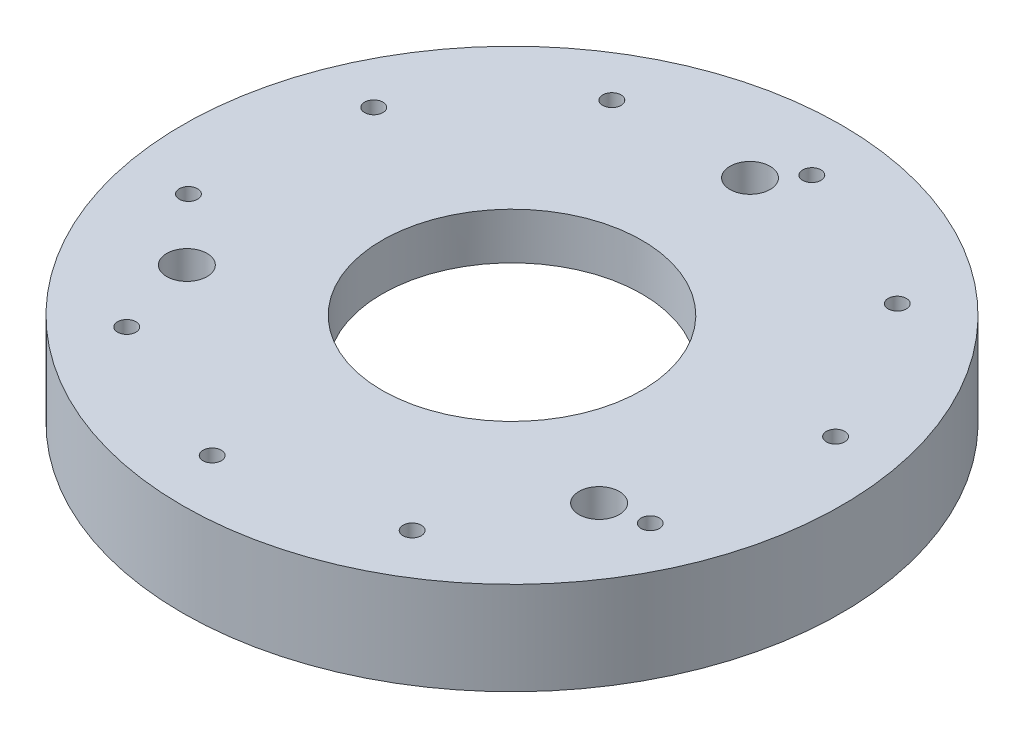
SolidWorks part; units mm, degrees
material "6061-T6 (SS)"
ref_plane "Front Plane" through (0, 0, 0) normal (0, 0, 1) x (1, 0, 0)
ref_plane "Top Plane" through (0, 0, 0) normal (0, 1, 0) x (1, 0, 0)
ref_plane "Right Plane" through (0, 0, 0) normal (1, 0, 0) x (0, 0, -1)
sketch "Sketch1" plane through (0, 0, 0) normal (0, 1, 0) x (1, 0, 0)
  line L0 (-36.436, -7.7447) -> (0, 0) construction
  line L1 (-28.1458, -16.25) -> (0, 0) construction
  circle A0 centre (0, 0) radius 45
  circle A1 centre (0, 32.5) radius 2.75
  circle A2 centre (0, 0) radius 32.5 construction
  circle A3 centre (28.1458, -16.25) radius 2.75
  circle A4 centre (-28.1458, -16.25) radius 2.75
  circle A5 centre (0, 0) radius 37.25 construction
  circle A6 centre (-36.436, -7.7447) radius 1.25
  circle A7 centre (-34.0296, 15.1509) radius 1.25
  circle A8 centre (-18.625, 32.2594) radius 1.25
  circle A9 centre (3.8937, 37.0459) radius 1.25
  circle A10 centre (24.9251, 27.6821) radius 1.25
  circle A11 centre (36.436, 7.7447) radius 1.25
  circle A12 centre (34.0296, -15.1509) radius 1.25
  circle A13 centre (18.625, -32.2594) radius 1.25
  circle A14 centre (-3.8937, -37.0459) radius 1.25
  circle A15 centre (-24.9251, -27.6821) radius 1.25
  circle A16 centre (0, 32.5) radius 4.25 construction
  circle A17 centre (28.1458, -16.25) radius 4.25 construction
  circle A18 centre (-28.1458, -16.25) radius 4.25 construction
  point P12 (0, 0)
  point P34 (0, 0)
  point P41 (0, 0)
  dimension "D1" = 90
  dimension "D2" = 65
  dimension "D3" = 5.5
  dimension "D5" = 74.5
  dimension "D6" = 2.5
  dimension "D9" = 8.5
  dimension "D7" = 18
  dimension "D4" = 3
  dimension "D8" = 10
  dimension "D10" = 3
extrude "Boss-Extrude1" add sketch "Sketch1" along normal blind 12.7
sketch "Sketch2" plane through (0, 12.7, 0) normal (0, 1, 0) x (1, 0, 0)
  circle A0 centre (0, 0) radius 17.75
  dimension "D1" = 35.5
extrude "Cut-Extrude1" cut sketch "Sketch2" against normal blind 6.35
sketch "Sketch3" plane through (0, 6.35, 0) normal (0, 1, 0) x (1, 0, 0)
  circle A0 centre (0, 0) radius 6
  dimension "D1" = 12
extrude "Cut-Extrude2" cut sketch "Sketch3" against normal through all
sketch "Sketch4" plane through (0, 0, 0) normal (0, -1, 0) x (1, 0, 0)
  circle A0 centre (0, 0) radius 28.5
  dimension "D1" = 57
extrude "Cut-Extrude3" cut sketch "Sketch4" against normal blind 6.35
sketch "Sketch6" plane through (0, 0, 0) normal (0, -1, 0) x (1, 0, 0)
  circle A0 centre (28.1458, 16.25) radius 4.25
  circle A1 centre (0, -32.5) radius 4.25
  circle A2 centre (-28.1458, 16.25) radius 4.25
  circle A3 centre (-28.1458, 16.25) radius 2.75 construction
  point P9 (0, 0)
  dimension "D1" = 8.5
  dimension "D2" = 3
extrude "Cut-Extrude4" cut sketch "Sketch6" against normal blind 6.35
